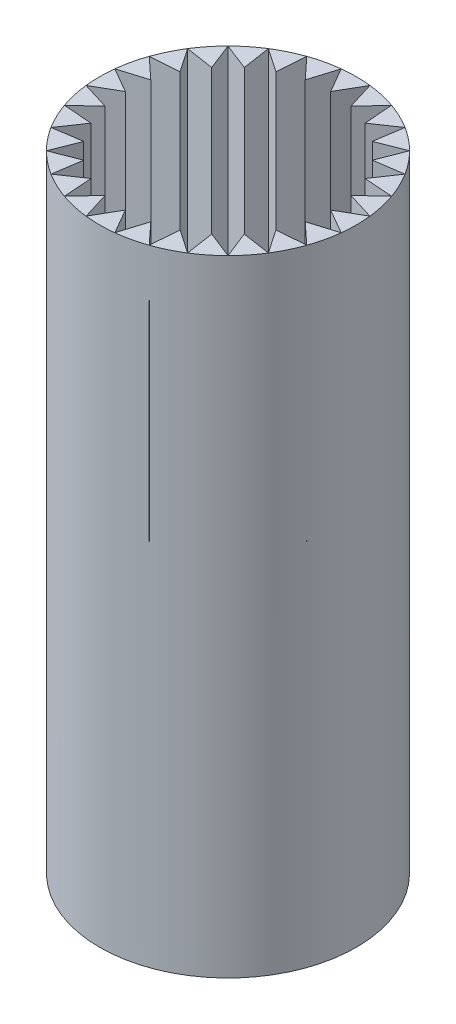
SolidWorks part; units mm, degrees
ref_plane "Front Plane" through (0, 0, 0) normal (0, 0, 1) x (1, 0, 0)
ref_plane "Top Plane" through (0, 0, 0) normal (0, 1, 0) x (1, 0, 0)
ref_plane "Right Plane" through (0, 0, 0) normal (1, 0, 0) x (0, 0, -1)
sketch "Sketch1" plane through (0, 0, 0) normal (0, 1, 0) x (1, 0, 0)
  line L0 (-1.8555, -1.6783) -> (1.8555, -1.6783)
  circle A0 centre (0, 0) radius 6.35
  arc A1 (1.8555, -1.6783) -> (-1.8555, -1.6783) centre (0, 0) ccw
  dimension "D1" = 12.7
  dimension "D2" = 5.0038
  dimension "D3" = 3.711
extrude "Boss-Extrude1" add sketch "Sketch1" along normal blind 18
sketch "Sketch2" plane through (0, 18, 0) normal (0, 1, 0) x (1, 0, 0)
  circle A0 centre (0, 0) radius 6.35
  dimension "D1" = 12.7
extrude "Boss-Extrude2" add sketch "Sketch2" along normal blind 0.254
sketch "Sketch4" plane through (0, 18.254, 0) normal (0, 1, 0) x (1, 0, 0)
  circle A0 centre (0, 0) radius 6.35
  dimension "D1" = 12.7
extrude "Boss-Extrude3" add sketch "Sketch4" along normal blind 12.7
sketch "Sketch7" plane through (0, 30.954, 0) normal (0, 1, 0) x (1, 0, 0)
  line L0 (0, -5.0782) -> (0, 6.35) construction
  line L1 (0, 5.0782) -> (0.7112, 6.31)
  line L2 (0, 5.0782) -> (-0.7112, 6.31)
  line L3 (1.13, 4.9509) -> (2.0975, 5.9936)
  line L4 (1.13, 4.9509) -> (0.7107, 6.3101)
  line L5 (2.2034, 4.5753) -> (3.3786, 5.3766)
  line L6 (2.2034, 4.5753) -> (2.0971, 5.9937)
  line L7 (3.1662, 3.9703) -> (4.4903, 4.49)
  line L8 (3.1662, 3.9703) -> (3.3782, 5.3768)
  line L9 (3.9703, 3.1662) -> (5.3768, 3.3782)
  line L10 (3.9703, 3.1662) -> (4.49, 4.4903)
  line L11 (4.5753, 2.2034) -> (5.9937, 2.0971)
  line L12 (4.5753, 2.2034) -> (5.3766, 3.3786)
  line L13 (4.9509, 1.13) -> (6.3101, 0.7107)
  line L14 (4.9509, 1.13) -> (5.9936, 2.0975)
  line L15 (5.0782, 0) -> (6.31, -0.7112)
  line L16 (5.0782, 0) -> (6.31, 0.7112)
  line L17 (4.9509, -1.13) -> (5.9936, -2.0975)
  line L18 (4.9509, -1.13) -> (6.3101, -0.7107)
  line L19 (4.5753, -2.2034) -> (5.3766, -3.3786)
  line L20 (4.5753, -2.2034) -> (5.9937, -2.0971)
  line L21 (3.9703, -3.1662) -> (4.49, -4.4903)
  line L22 (3.9703, -3.1662) -> (5.3768, -3.3782)
  line L23 (3.1662, -3.9703) -> (3.3782, -5.3768)
  line L24 (3.1662, -3.9703) -> (4.4903, -4.49)
  line L25 (2.2034, -4.5753) -> (2.0971, -5.9937)
  line L26 (2.2034, -4.5753) -> (3.3786, -5.3766)
  line L27 (1.13, -4.9509) -> (0.7107, -6.3101)
  line L28 (1.13, -4.9509) -> (2.0975, -5.9936)
  line L29 (0, -5.0782) -> (-0.7112, -6.31)
  line L30 (0, -5.0782) -> (0.7112, -6.31)
  line L31 (-1.13, -4.9509) -> (-2.0975, -5.9936)
  line L32 (-1.13, -4.9509) -> (-0.7107, -6.3101)
  line L33 (-2.2034, -4.5753) -> (-3.3786, -5.3766)
  line L34 (-2.2034, -4.5753) -> (-2.0971, -5.9937)
  line L35 (-3.1662, -3.9703) -> (-4.4903, -4.49)
  line L36 (-3.1662, -3.9703) -> (-3.3782, -5.3768)
  line L37 (-3.9703, -3.1662) -> (-5.3768, -3.3782)
  line L38 (-3.9703, -3.1662) -> (-4.49, -4.4903)
  line L39 (-4.5753, -2.2034) -> (-5.9937, -2.0971)
  line L40 (-4.5753, -2.2034) -> (-5.3766, -3.3786)
  line L41 (-4.9509, -1.13) -> (-6.3101, -0.7107)
  line L42 (-4.9509, -1.13) -> (-5.9936, -2.0975)
  line L43 (-5.0782, 0) -> (-6.31, 0.7112)
  line L44 (-5.0782, 0) -> (-6.31, -0.7112)
  line L45 (-4.9509, 1.13) -> (-5.9936, 2.0975)
  line L46 (-4.9509, 1.13) -> (-6.3101, 0.7107)
  line L47 (-4.5753, 2.2034) -> (-5.3766, 3.3786)
  line L48 (-4.5753, 2.2034) -> (-5.9937, 2.0971)
  line L49 (-3.9703, 3.1662) -> (-4.49, 4.4903)
  line L50 (-3.9703, 3.1662) -> (-5.3768, 3.3782)
  line L51 (-3.1662, 3.9703) -> (-3.3782, 5.3768)
  line L52 (-3.1662, 3.9703) -> (-4.4903, 4.49)
  line L53 (-2.2034, 4.5753) -> (-2.0971, 5.9937)
  line L54 (-2.2034, 4.5753) -> (-3.3786, 5.3766)
  line L55 (-1.13, 4.9509) -> (-0.7107, 6.3101)
  line L56 (-1.13, 4.9509) -> (-2.0975, 5.9936)
  line L57 (0, -5.0782) -> (0, -6.35) construction
  circle A0 centre (0, 0) radius 6.35
  point P90 (0, 0)
  dimension "D1" = 12.7
  dimension "D2" = 1.4224
  dimension "D3" = 30
  dimension "D4" = 28
extrude "Cut-Extrude4" cut sketch "Sketch7" against normal blind 12.7 contours L55 L56 L53 L54 L51 L52 L49 L50 L47 L48 L45 L46 L43 L44 L41 L42 L39 L40 L37 L38 L35 L36 L33 L34 L31 L32 L29 L30 L27 L28 L25 L26 L23 L24 L21 L22 L19 L20 L17 L18 L15 L16 L13 L14 L11 L12 L9 L10 L7 L8 L5
